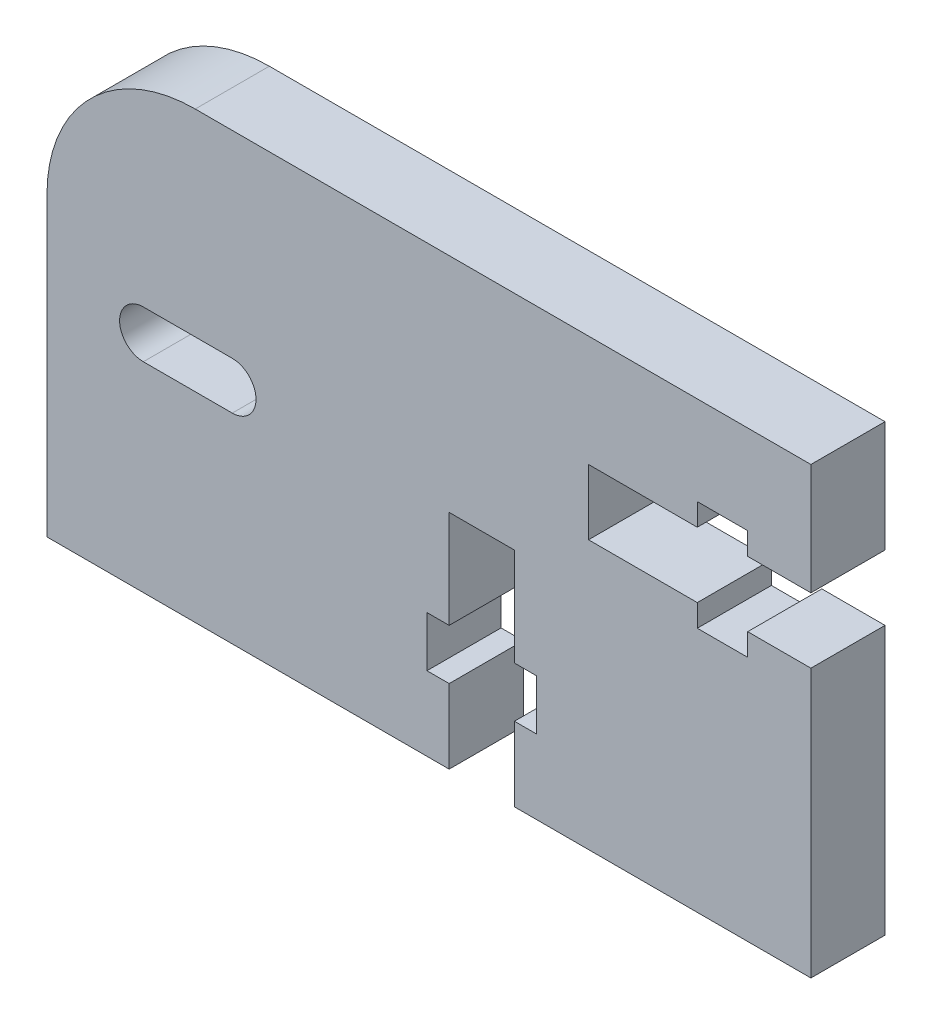
SolidWorks part; units mm, degrees
ref_plane "Front Plane" through (0, 0, 0) normal (0, 0, 1) x (1, 0, 0)
ref_plane "Top Plane" through (0, 0, 0) normal (0, 1, 0) x (1, 0, 0)
ref_plane "Right Plane" through (0, 0, 0) normal (1, 0, 0) x (0, 0, -1)
sketch "Sketch1" plane through (0, 0, 0) normal (0, 0, 1) x (1, 0, 0)
  line L1 (-23, 10) -> (28.53, 10)
  line L2 (-23, 10) -> (-23, -20)
  line L3 (-23, -20) -> (28.53, -20)
  line L4 (28.53, 10) -> (28.53, -20)
  dimension "D1" = 51.53
  dimension "30" = 30
  dimension "D3" = 23
  dimension "D4" = 10
extrude "Boss-Extrude1" add sketch "Sketch1" along normal blind 5
sketch "Sketch2" plane through (0, 0, 5) normal (0, 0, 1) x (1, 0, 0)
  line L0 (-23, -20) -> (28.53, -20) construction
  line L1 (13.53, -1.9) -> (20.8659, -1.9)
  line L2 (28.53, -1.9) -> (28.53, 2.5)
  line L3 (28.53, 2.5) -> (24.2659, 2.5)
  line L4 (13.53, -1.9) -> (13.53, 2.5)
  line L5 (20.8659, -1.9) -> (20.8659, -3.4)
  line L6 (20.8659, -3.4) -> (24.2659, -3.4)
  line L7 (24.2659, -3.4) -> (24.2659, -1.9)
  line L8 (20.8659, 2.5) -> (20.8659, 4)
  line L9 (20.8659, 4) -> (24.2659, 4)
  line L10 (24.2659, 4) -> (24.2659, 2.5)
  line L11 (24.2659, -1.9) -> (28.53, -1.9)
  line L12 (20.8659, 2.5) -> (13.53, 2.5)
  line L13 (28.53, -20) -> (28.53, 10) construction
  line L14 (28.53, 10) -> (-23, 10) construction
  line L15 (-2.6961, 5.9568) -> (-2.6961, -8.8884) construction
  line L16 (4.13, -5) -> (4.13, -11.6)
  line L17 (4.13, -20) -> (8.53, -20)
  line L18 (8.53, -20) -> (8.53, -15)
  line L19 (4.13, -5) -> (8.53, -5)
  line L20 (4.13, -11.6) -> (2.63, -11.6)
  line L21 (2.63, -11.6) -> (2.63, -15)
  line L22 (2.63, -15) -> (4.13, -15)
  line L23 (8.53, -11.6) -> (10.03, -11.6)
  line L24 (10.03, -11.6) -> (10.03, -15)
  line L25 (10.03, -15) -> (8.53, -15)
  line L26 (4.13, -15) -> (4.13, -20)
  line L27 (8.53, -11.6) -> (8.53, -5)
  dimension "D1" = 4.4
  dimension "D2" = 1.5
  dimension "D3" = 3.4
  dimension "D4" = 7.5
  dimension "D5" = 15
  dimension "D6" = 5
  dimension "D7" = 15
  dimension "D8" = 20
  dimension "D9" = 4.4
  dimension "D10" = 1.5
  dimension "D11" = 1.5
  dimension "D12" = 7.4
  dimension "D13" = 3.4
extrude "Cut-Extrude1" cut sketch "Sketch2" against normal blind 5
sketch "Sketch4" plane through (0, 0, 5) normal (0, 0, 1) x (1, 0, 0)
  line L0 (28.53, 10) -> (-23, 10) construction
  circle A1 centre (-13.8996, -4.9036) radius 1.5
  dimension "D3" = 3
  dimension "D1" = 14.9036
  dimension "D2" = 13.8996
extrude "Cut-Extrude3" [suppressed] cut sketch "Sketch4" against normal blind 5
sketch "Sketch5" plane through (0, 0, 5) normal (0, 0, 1) x (1, 0, 0)
  circle A1 centre (-12.2019, -4.8556) radius 1.7
extrude "Cut-Extrude4" [suppressed] cut sketch "Sketch5" against normal blind 10
fillet "Fillet1" radius 10 1 edges at (-23, 10, 2.5)
sketch "Sketch6" plane through (0, 0, 5) normal (0, 0, 1) x (1, 0, 0)
  line L0 (-16.5009, -4.9145) -> (-10.5009, -4.9145) construction
  line L1 (-16.5009, -3.3145) -> (-10.5009, -3.3145)
  line L2 (-16.5009, -6.5145) -> (-10.5009, -6.5145)
  line L3 (28.53, 10) -> (-13, 10) construction
  line L4 (-23, 0) -> (-23, -20) construction
  arc A0 (-16.5009, -3.3145) -> (-16.5009, -6.5145) centre (-16.5009, -4.9145) ccw
  arc A2 (-10.5009, -6.5145) -> (-10.5009, -3.3145) centre (-10.5009, -4.9145) ccw
  point P4 (-13.5009, -4.9145)
  dimension "D1" = 3.2
  dimension "D2" = 14.9145
  dimension "D3" = 6.4991
  dimension "D4" = 6
extrude "Cut-Extrude5" cut sketch "Sketch6" against normal blind 10
